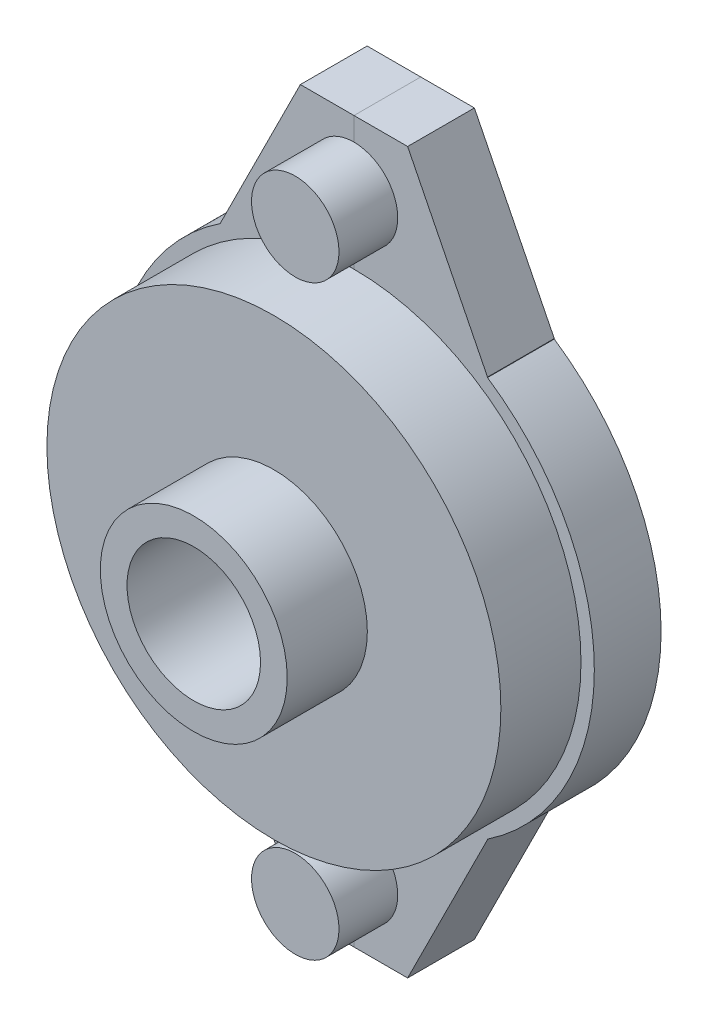
SolidWorks part; units mm, degrees
ref_plane "정면" through (0, 0, 0) normal (0, 0, 1) x (1, 0, 0)
ref_plane "윗면" through (0, 0, 0) normal (0, 1, 0) x (1, 0, 0)
ref_plane "우측면" through (0, 0, 0) normal (1, 0, 0) x (0, 0, -1)
sketch "스케치1" plane through (0, 0, 0) normal (0, 0, 1) x (1, 0, 0)
  circle A0 centre (0, 0) radius 17
  dimension "D1" = 34
extrude "보스-돌출1" add sketch "스케치1" along normal blind 6
sketch "스케치2" plane through (0, 0, 6) normal (0, 0, 1) x (1, 0, 0)
  circle A0 centre (0, 0) radius 7
  dimension "D1" = 14
extrude "보스-돌출2" add sketch "스케치2" along normal blind 6
sketch "스케치3" plane through (0, 0, 0) normal (0, 0, -1) x (-1, 0, 0)
  circle A0 centre (0, 0) radius 18
  dimension "D1" = 36
extrude "보스-돌출3" add sketch "스케치3" along normal blind 5
sketch "스케치8" plane through (0, 0, -5) normal (0, 0, -1) x (-1, 0, 0)
  line L0 (-10, 14.9666) -> (10, 14.9666) construction
  line L1 (-10, 14.9666) -> (-10, 26.9666)
  line L2 (-10, 26.9666) -> (10, 26.9666)
  line L3 (10, 26.9666) -> (10, 14.9666)
  arc A0 (-10, 14.9666) -> (10, 14.9666) centre (0, 0) cw
  circle A1 centre (0, 0) radius 18 construction
  dimension "D1" = 20
  dimension "D2" = 12
extrude "보스-돌출6" add sketch "스케치8" against normal blind 5
sketch "스케치5" plane through (0, 0, 0) normal (0, 0, 1) x (1, 0, 0)
  line L0 (-10, 27) -> (-10, 15)
  line L3 (-10, 15) -> (-4, 27)
  line L5 (-4, 27) -> (-10, 27)
  line L6 (0, -9.35) -> (0, 9.35) construction
  line L7 (4, 27) -> (10, 27)
  line L8 (10, 15) -> (4, 27)
  line L9 (10, 27) -> (10, 15)
  dimension "D1" = 8
extrude "컷-돌출1" cut sketch "스케치5" against normal blind 8
sketch "스케치6" plane through (0, 0, 0) normal (0, 0, 1) x (1, 0, 0)
  line L1 (-4.0167, 26.9666) -> (4.0167, 26.9666) construction
  circle A0 centre (0, 21.9666) radius 3.275
  dimension "D2" = 6.55
  dimension "D1" = 5
extrude "보스-돌출5" add sketch "스케치6" along normal blind 4.4
mirror "대칭 복사6" about plane through (0, 0, 0) normal (0, 1, 0) of "보스-돌출5", "컷-돌출1", "보스-돌출6"
sketch "스케치9" plane through (0, 0, 12) normal (0, 0, 1) x (1, 0, 0)
  circle A0 centre (0, 0) radius 5
extrude "컷-돌출3" cut sketch "스케치9" against normal through all
sketch "스케치10" plane through (0, 0, -5) normal (0, 0, -1) x (-1, 0, 0)
  circle A0 centre (0, 0) radius 8.6
  circle A1 centre (0, 0) radius 13.6
  arc A2 (-10, 14.9666) -> (-10, -14.9666) centre (0, 0) ccw construction
  dimension "D1" = 4.4
  dimension "D2" = 5
extrude "컷-돌출4" cut sketch "스케치10" against normal blind 3
sketch "스케치11" plane through (0, 0, -5) normal (0, 0, -1) x (-1, 0, 0)
  circle A0 centre (0, 0) radius 8.6
extrude "컷-돌출5" cut sketch "스케치11" against normal blind 2.8
split line "분할선1"
